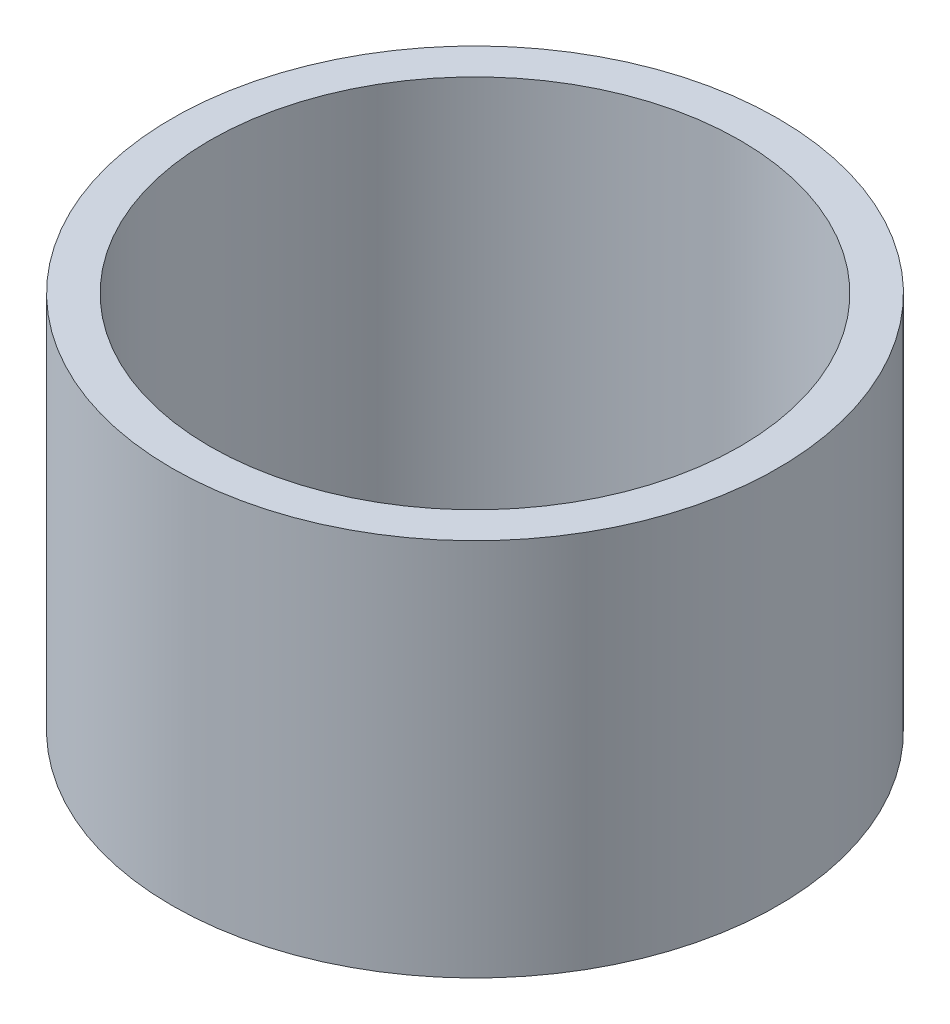
SolidWorks part; units mm, degrees
ref_plane "Front Plane" through (0, 0, 0) normal (0, 0, 1) x (1, 0, 0)
ref_plane "Top Plane" through (0, 0, 0) normal (0, 1, 0) x (1, 0, 0)
ref_plane "Right Plane" through (0, 0, 0) normal (1, 0, 0) x (0, 0, -1)
sketch "Sketch1" plane through (0, 0, 0) normal (0, 1, 0) x (1, 0, 0)
  circle A0 centre (0, 0) radius 7
  circle A1 centre (0, 0) radius 8
  dimension "D1" = 14
  dimension "D2" = 16
extrude "Boss-Extrude1" add sketch "Sketch1" along normal blind 10
